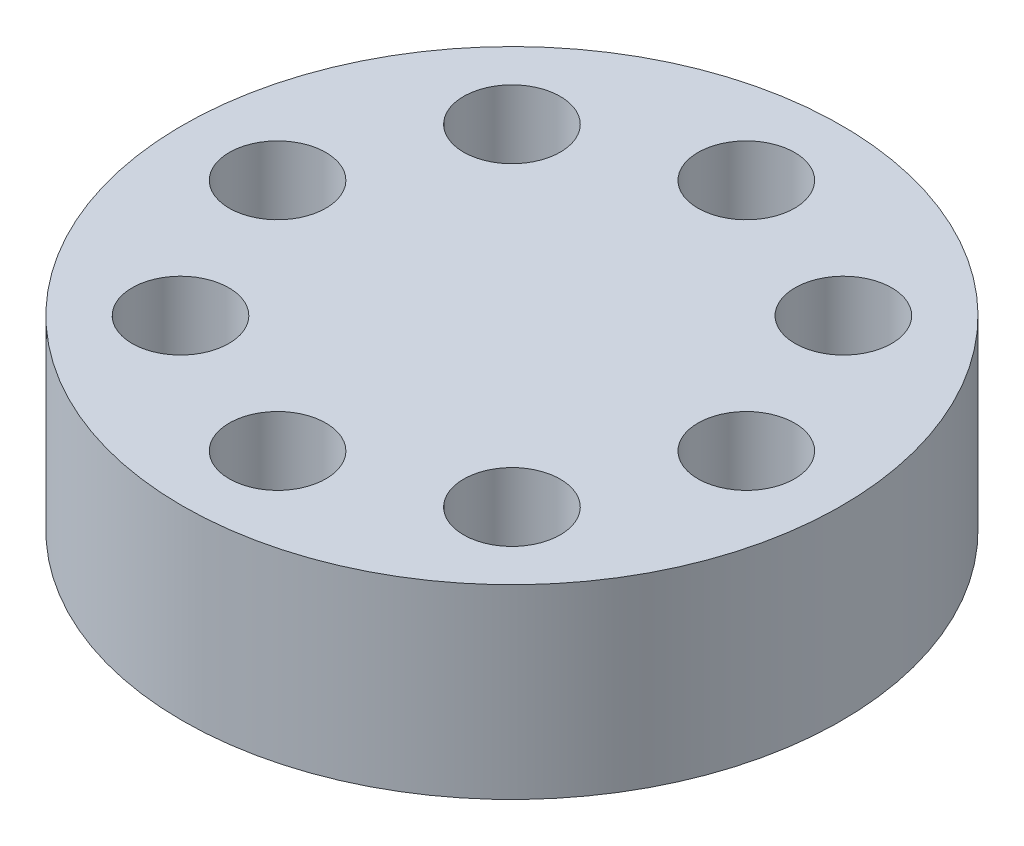
SolidWorks part; units mm, degrees
ref_plane "Front Plane" through (0, 0, 0) normal (0, 0, 1) x (1, 0, 0)
ref_plane "Top Plane" through (0, 0, 0) normal (0, 1, 0) x (1, 0, 0)
ref_plane "Right Plane" through (0, 0, 0) normal (1, 0, 0) x (0, 0, -1)
sketch "Sketch1" plane through (0, 0, 0) normal (0, 1, 0) x (1, 0, 0)
  circle A0 centre (0, 0) radius 22.5
  dimension "D1" = 45
extrude "Boss-Extrude1" add sketch "Sketch1" along normal blind 12.7
sketch "Sketch2" plane through (0, 12.7, 0) normal (0, 1, 0) x (1, 0, 0)
  circle A0 centre (0, 0) radius 16 construction
  circle A1 centre (-16, 0) radius 3.3
  circle A2 centre (-11.3137, 11.3137) radius 3.3
  circle A3 centre (0, 16) radius 3.3
  circle A4 centre (11.3137, 11.3137) radius 3.3
  circle A5 centre (16, 0) radius 3.3
  circle A6 centre (11.3137, -11.3137) radius 3.3
  circle A7 centre (0, -16) radius 3.3
  circle A8 centre (-11.3137, -11.3137) radius 3.3
  point P21 (0, 0)
  dimension "D1" = 32
  dimension "D2" = 6.6
  dimension "D3" = 8
extrude "Cut-Extrude1" cut sketch "Sketch2" against normal through all
equation "\"L1L\"=500"
equation "\"L1Thick\"=6.35"
equation "\"Harm-Drive-Outer\"=74.5"
equation "\"L1-Spacing\"=115.65"
equation "\"L-Bracket-HoleToWall\"=12.5"
equation "\"L-Bracket-HoleToSide\"=11"
equation "\"Bracket-Hole-D\"=6.8"
equation "\"D1@Boss-Extrude1\"=\"L1Thick\"*2"
